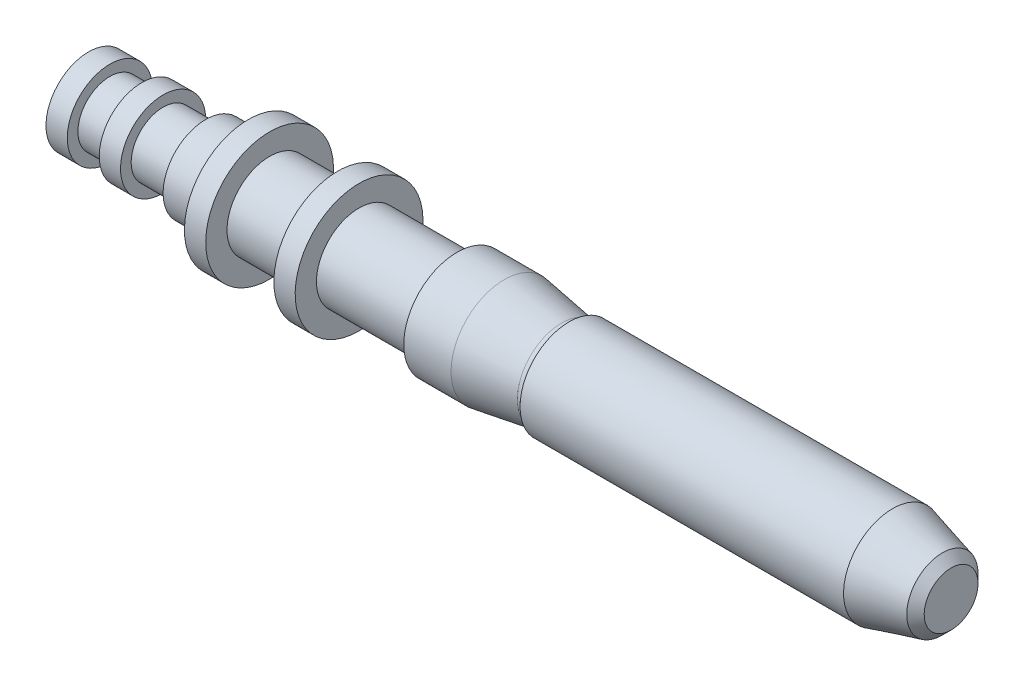
SolidWorks part; units mm, degrees
material "PEEK ZENIVA"
ref_plane "Front Plane" through (0, 0, 0) normal (0, 0, 1) x (1, 0, 0)
ref_plane "Top Plane" through (0, 0, 0) normal (0, 1, 0) x (1, 0, 0)
ref_plane "Right Plane" through (0, 0, 0) normal (1, 0, 0) x (0, 0, -1)
sketch "Sketch1" plane through (0, 0, 0) normal (0, 0, 1) x (1, 0, 0)
  line L0 (6.9558, 0.508) -> (6.9558, 0)
  line L1 (16.5443, 0.5842) -> (17.2428, 0.397)
  line L2 (-986.2846, 0) -> (49013.7154, 0) construction
  line L3 (12.6861, 0.5842) -> (16.5443, 0.5842)
  line L6 (11.35, 0.508) -> (11.35, 0.635)
  line L7 (-986.2846, 0.5842) -> (49013.7154, 0.5842) construction
  line L8 (8.3528, 0.508) -> (8.8608, 0.508)
  line L10 (11.9139, 0.635) -> (12.6483, 0.5187)
  line L11 (12.6861, 0.5842) -> (12.6483, 0.5187)
  line L12 (10.1816, 0.508) -> (11.35, 0.508)
  line L13 (-986.2846, 0.508) -> (49013.7154, 0.508) construction
  line L14 (9.1148, 0.508) -> (9.9276, 0.508)
  line L15 (7.5908, 0.381) -> (7.5908, 0.508)
  line L16 (7.8448, 0.381) -> (7.8448, 0.508)
  line L18 (11.35, 0.635) -> (11.9139, 0.635)
  line L19 (17.2428, 0) -> (6.9558, 0)
  line L20 (7.5908, -999.619) -> (7.5908, 49000.381) construction
  line L21 (7.8448, -999.619) -> (7.8448, 49000.381) construction
  line L22 (-986.2846, 0.635) -> (49013.7154, 0.635) construction
  line L23 (17.2428, 0.397) -> (17.2428, 0)
  line L25 (9.1148, 0.508) -> (9.1148, 0.762)
  line L26 (10.1816, 0.508) -> (10.1816, 0.762)
  line L27 (9.9276, 0.508) -> (9.9276, 0.762)
  line L28 (8.8608, 0.508) -> (8.8608, 0.762)
  line L29 (8.8608, 0.762) -> (9.1148, 0.762)
  line L31 (8.8608, -999.4285) -> (8.8608, 49000.5715) construction
  line L32 (9.1148, -999.4285) -> (9.1148, 49000.5715) construction
  line L33 (9.9276, -999.4285) -> (9.9276, 49000.5715) construction
  line L34 (10.1816, -999.4285) -> (10.1816, 49000.5715) construction
  line L35 (9.9276, 0.762) -> (10.1816, 0.762)
  line L36 (-986.2846, 0.762) -> (49013.7154, 0.762) construction
  line L40 (7.2098, 0.508) -> (6.9558, 0.508)
  line L41 (7.8448, 0.508) -> (7.5908, 0.508)
  line L52 (7.2098, 0.381) -> (7.2098, 0.508)
  line L56 (8.3528, 0.381) -> (8.3528, 0.508)
  line L58 (7.8448, 0.381) -> (8.3528, 0.381)
  line L60 (7.2098, 0.381) -> (7.5908, 0.381)
  point P9 (17.2428, -1002.1771)
  point P10 (14.1948, -1002.1771)
  point P11 (17.2428, 48997.8229)
  point P13 (14.1948, 48997.8229)
  point P14 (13.0518, -1002.1771)
  point P15 (13.0518, 48997.8229)
  point P16 (12.7216, -1002.1771)
  point P18 (12.7216, 48997.8229)
  point P19 (11.7818, -1002.1771)
  point P20 (11.7818, 48997.8229)
  point P58 (-999.3848, 0.2032)
  point P61 (49000.6152, 0.2032)
  point P62 (0.7328, -999.873)
  point P63 (0.7328, 49000.127)
  point P64 (1.2408, -999.873)
  point P65 (1.2408, 49000.127)
  point P66 (0.8598, -999.873)
  point P67 (0.8598, 49000.127)
  point P68 (1.3678, -999.873)
  point P69 (1.3678, 49000.127)
  point P71 (10.7658, -999.5555)
  point P73 (10.7658, 49000.4445)
  point P75 (-999.3848, 0.1778)
  point P77 (49000.6152, 0.1778)
  dimension "D3" = 0.508
  dimension "D4" = 1.905
  dimension "D5" = 2.9718
  dimension "D6" = 10.287
  dimension "D7" = 0.6985
  dimension "D8" = 15
  dimension "D9" = 1.397
  dimension "D10" = 0.508
  dimension "D11" = 0.381
  dimension "D12" = 0.254
  dimension "D13" = 5.8928
  dimension "D14" = 4.9581
  dimension "D18" = 5.7302
  dimension "D19" = 60
  dimension "D20" = 0.127
  dimension "D22" = 0.254
  dimension "D26" = 0.635
  dimension "D15" = 0.254
  dimension "D16" = 0.254
  dimension "D17" = 0.762
revolve "Revolve1" add sketch "Sketch1" angle 360 about L2
fillet "Fillet1" radius 0.0762 1 edges at (12.6483, -0.5187, 0)
chamfer "Chamfer1" distance 0.0762 angle 45 1 edges at (17.2428, -0.397, 0)
